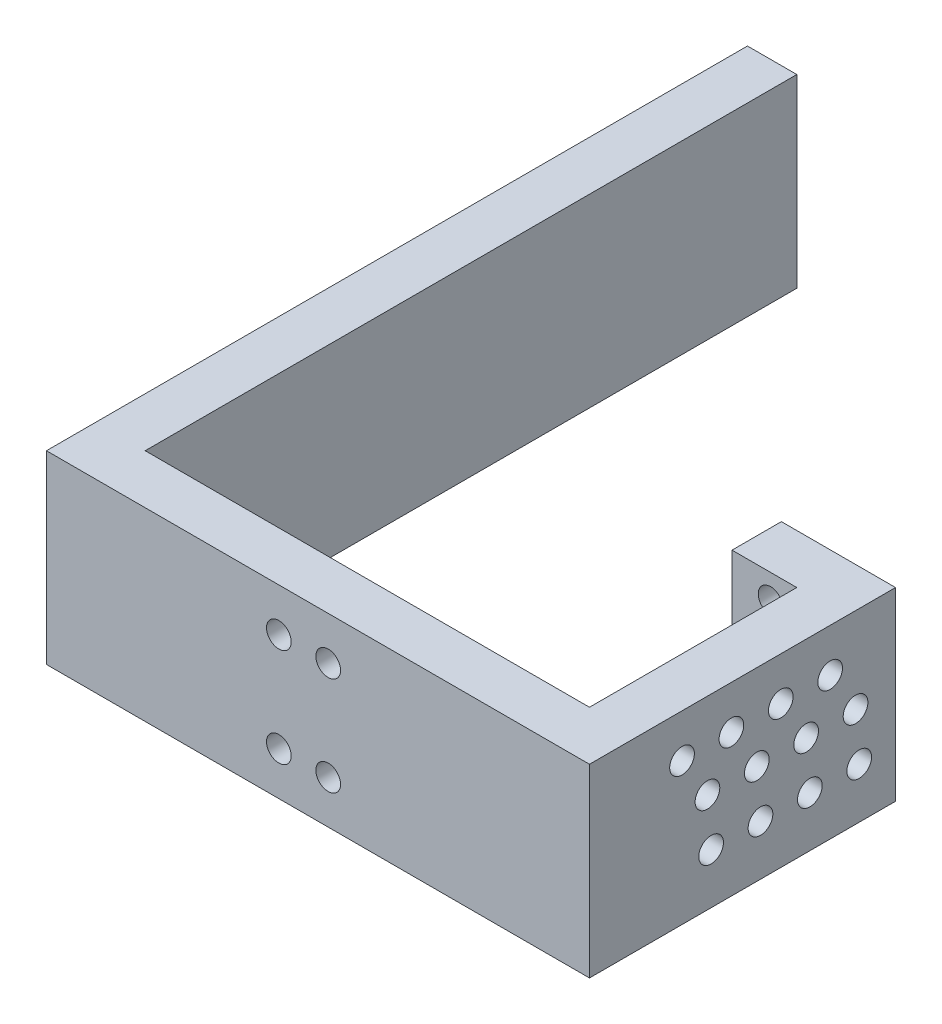
SolidWorks part; units mm, degrees
ref_plane "前基準面" through (0, 0, 0) normal (0, 0, 1) x (1, 0, 0)
ref_plane "上基準面" through (0, 0, 0) normal (0, 1, 0) x (1, 0, 0)
ref_plane "右基準面" through (0, 0, 0) normal (1, 0, 0) x (0, 0, -1)
sketch "草圖1" plane through (0, 0, 0) normal (0, 0, 1) x (1, 0, 0)
  line L1 (0, 0) -> (72, 0)
  line L2 (0, 0) -> (0, 30)
  line L3 (0, 30) -> (72, 30)
  line L4 (72, 0) -> (72, 30)
  dimension "D1" = 72
  dimension "D2" = 30
extrude "填料-伸長1" add sketch "草圖1" along normal blind 8
sketch "草圖2" plane through (0, 0, 0) normal (-1, 0, 0) x (0, 0, 1)
  line L0 (8, 30) -> (8, 0) construction
  line L1 (8, 30) -> (-105.6, 30)
  line L2 (8, 30) -> (8, 0)
  line L3 (8, 0) -> (-105.6, 0)
  line L4 (-105.6, 30) -> (-105.6, 0)
  dimension "D1" = 30
  dimension "D2" = 113.6
extrude "填料-伸長2" add sketch "草圖2" along normal blind 8
sketch "草圖3" plane through (72, 0, 0) normal (1, 0, 0) x (0, 0, -1)
  line L5 (-8, 30) -> (41.6, 30)
  line L6 (-8, 30) -> (-8, 0)
  line L7 (-8, 0) -> (41.6, 0)
  line L8 (41.6, 30) -> (41.6, 0)
  dimension "D1" = 49.6
extrude "填料-伸長3" add sketch "草圖3" along normal blind 8
sketch "草圖5" plane through (0, 0, -41.6) normal (0, 0, -1) x (-1, 0, 0)
  line L5 (-80, 30) -> (-61.5, 30)
  line L6 (-80, 30) -> (-80, 0)
  line L11 (-80, 0) -> (-61.5, 0)
  line L12 (-61.5, 30) -> (-61.5, 0)
  circle A6 centre (-67.75, 26) radius 2
  circle A7 centre (-67.75, 18) radius 2
  circle A8 centre (-67.75, 10) radius 2
  dimension "D3" = 8
  dimension "D1" = 18.5
  dimension "D2" = 30
  dimension "D4" = 8
  dimension "D5" = 10
  dimension "D6" = 6.25
  dimension "D7" = 6.25
  dimension "D8" = 6.25
extrude "填料-伸長4" add sketch "草圖5" against normal blind 8
sketch "草圖10" plane through (0, 0, 8) normal (0, 0, 1) x (1, 0, 0)
  line L0 (-8, 0) -> (-8, 30) construction
  line L1 (-8, 0) -> (80, 0) construction
  circle A0 centre (29.66, 23) radius 2
  circle A1 centre (37.66, 23) radius 2
  circle A2 centre (37.66, 7) radius 2
  circle A3 centre (29.66, 7) radius 2
  dimension "D1" = 37.66
  dimension "D2" = 37.66
  dimension "D3" = 8
  dimension "D4" = 8
  dimension "D5" = 16
  dimension "D6" = 16
  dimension "D7" = 7
extrude "除料-伸長3" cut sketch "草圖10" against normal blind 15.5
sketch "草圖11" plane through (-8, 0, 0) normal (-1, 0, 0) x (0, 0, 1)
  line L0 (8, 30) -> (-105.6, 30) construction
  line L1 (8, 0) -> (8, 30) construction
  circle A0 centre (-31, 23) radius 2
  circle A1 centre (-31, 15) radius 2
  circle A2 centre (-31, 7) radius 2
  circle A3 centre (-23, 23) radius 2
  circle A4 centre (-23, 15) radius 2
  circle A5 centre (-23, 7) radius 2
  circle A6 centre (-15, 23) radius 2
  circle A7 centre (-15, 15) radius 2
  circle A8 centre (-15, 7) radius 2
  circle A9 centre (-7, 23) radius 2
  circle A10 centre (-7, 15) radius 2
  circle A11 centre (-7, 7) radius 2
  dimension "D1" = 8
  dimension "D2" = 8
  dimension "D3" = 7
  dimension "D4" = 15
  dimension "D5" = 4
extrude "除料-伸長4" cut sketch "草圖11" against normal blind 6
sketch "草圖12" plane through (0, 0, -105.6) normal (0, 0, -1) x (-1, 0, 0)
  line L0 (8, 30) -> (0, 30) construction
  line L2 (0, 30) -> (0, 0) construction
  circle A0 centre (3, 23) radius 1.8
  circle A1 centre (3, 15) radius 1.8
  circle A2 centre (3, 7) radius 1.8
  dimension "D1" = 8
  dimension "D5" = 3.6
  dimension "D6" = 3.6
  dimension "D7" = 3.6
  dimension "D2" = 8
  dimension "D3" = 7
  dimension "D4" = 3
extrude "除料-伸長6" cut sketch "草圖12" against normal blind 8
sketch "草圖13" plane through (80, 0, 0) normal (1, 0, 0) x (0, 0, -1)
  line L0 (41.6, 30) -> (-8, 30) construction
  line L1 (-8, 30) -> (-8, 0) construction
  circle A0 centre (7, 23) radius 2
  circle A1 centre (11.116, 16.1401) radius 2
  circle A2 centre (11.713, 8.1624) radius 2
  circle A3 centre (15, 23) radius 2
  circle A4 centre (19.116, 16.1401) radius 2
  circle A5 centre (19.713, 8.1624) radius 2
  circle A6 centre (23, 23) radius 2
  circle A7 centre (27.116, 16.1401) radius 2
  circle A8 centre (27.713, 8.1624) radius 2
  circle A9 centre (31, 23) radius 2
  circle A10 centre (35.116, 16.1401) radius 2
  circle A11 centre (35.713, 8.1624) radius 2
  dimension "D1" = 8
  dimension "D2" = 8
  dimension "D3" = 7
  dimension "D4" = 15
  dimension "D5" = 4
extrude "除料-伸長7" cut sketch "草圖13" against normal blind 6
